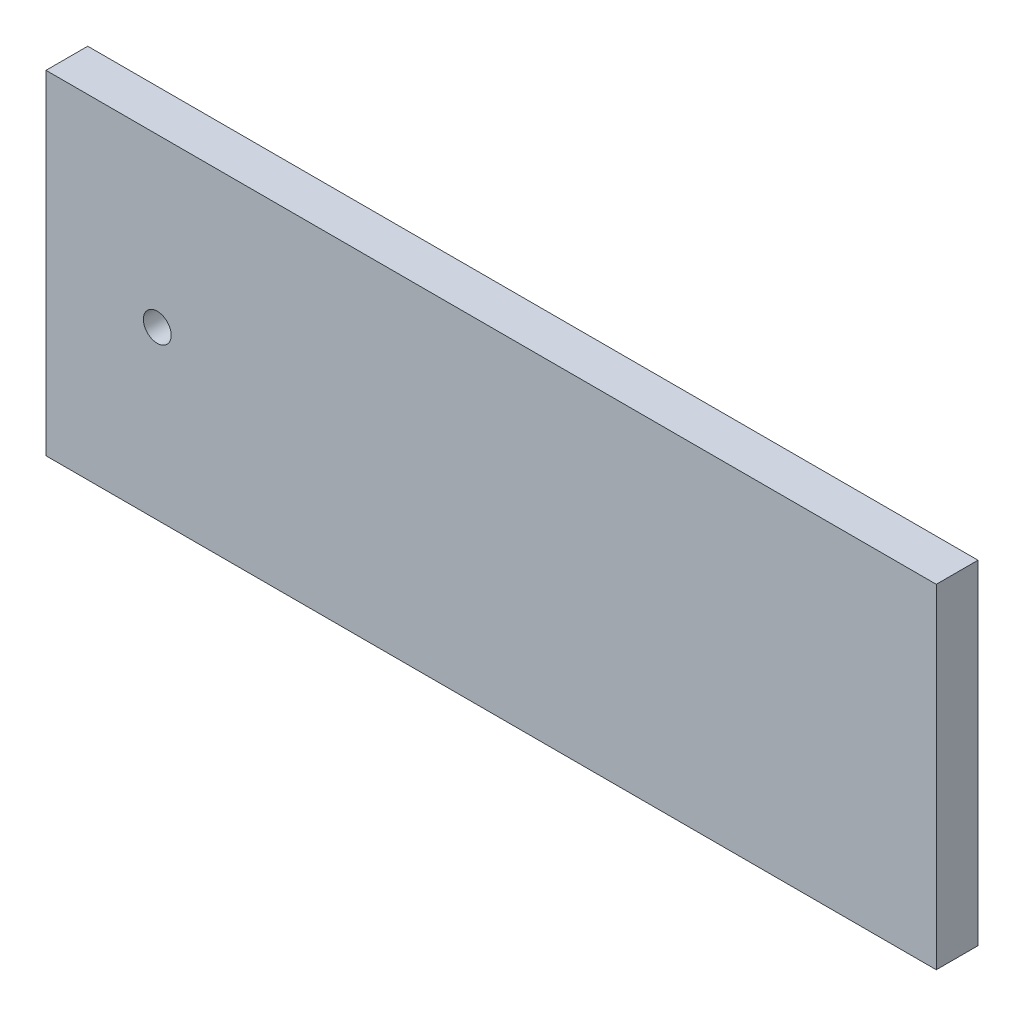
SolidWorks part; units mm, degrees
ref_plane "Front Plane" through (0, 0, 0) normal (0, 0, 1) x (1, 0, 0)
ref_plane "Top Plane" through (0, 0, 0) normal (0, 1, 0) x (1, 0, 0)
ref_plane "Right Plane" through (0, 0, 0) normal (1, 0, 0) x (0, 0, -1)
sketch "Sketch1" plane through (0, 0, 0) normal (0, 0, 1) x (1, 0, 0)
  line L1 (0, 0) -> (203.2, 0)
  line L2 (0, 0) -> (0, 76.2)
  line L3 (0, 76.2) -> (203.2, 76.2)
  line L4 (203.2, 0) -> (203.2, 76.2)
extrude "plate" add sketch "Sketch1" along normal blind 9.525
sketch "Sketch2" plane through (0, 0, 0) normal (0, 0, 1) x (1, 0, 0)
  circle A0 centre (25.4, 38.1) radius 3.175
extrude "seed_hole" cut sketch "Sketch2" along normal through all
